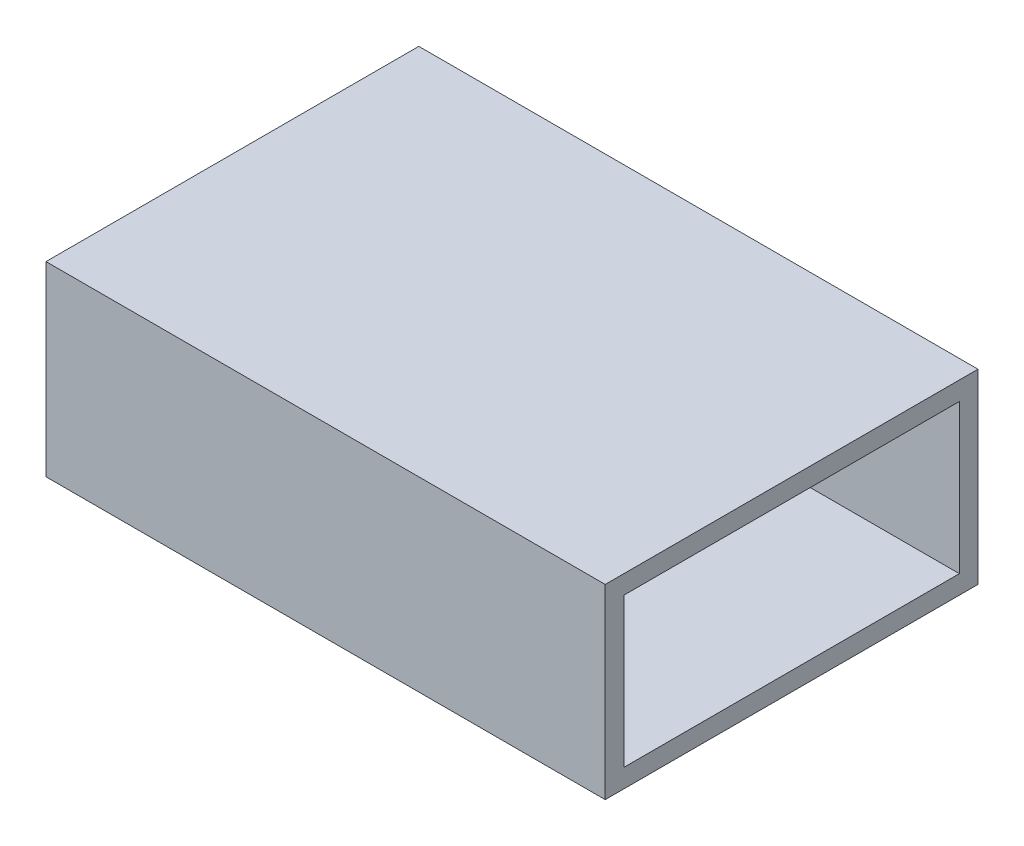
SolidWorks part; units mm, degrees
ref_plane "Front Plane" through (0, 0, 0) normal (0, 0, 1) x (1, 0, 0)
ref_plane "Top Plane" through (0, 0, 0) normal (0, 1, 0) x (1, 0, 0)
ref_plane "Right Plane" through (0, 0, 0) normal (1, 0, 0) x (0, 0, -1)
sketch3d "3DSketch1"
  line L0 (-38.1, 0, 0) -> (38.1, 0, 0)
  point P4 (0, 0, 0)
  dimension "D1" = 76.2
other "Versaframe VERSAFRAME 2 X 1 X 0.1 (1)"
ref_plane "Plane1" through (-38.1, 0, 0) normal (1, 0, 0) x (0, 1, 0)
sketch "Sketch1" plane through (-38.1, 0, 0) normal (1, 0, 0) x (0, 1, 0)
  line L0 (-10.16, 22.86) -> (-10.16, -22.86)
  line L1 (-12.7, 25.4) -> (12.7, 25.4)
  line L2 (-12.7, 25.4) -> (-12.7, -25.4)
  line L3 (-12.7, -25.4) -> (12.7, -25.4)
  line L4 (12.7, 25.4) -> (12.7, -25.4)
  line L5 (-12.7, 25.4) -> (12.7, -25.4) construction
  line L6 (-12.7, -25.4) -> (12.7, 25.4) construction
  line L7 (-10.16, -22.86) -> (10.16, -22.86)
  line L8 (10.16, 22.86) -> (10.16, -22.86)
  line L9 (-10.16, 22.86) -> (10.16, 22.86)
  line L10 (0, 25.4) -> (0, -25.4) construction
  line L12 (12.7, 0) -> (-12.7, 0) construction
  point P0 (0, 0)
  point P12 (0, 22.86)
  point P15 (-10.16, 0)
  point P16 (10.16, 0)
  point P17 (0, -22.86)
  point P18 (0, 0)
  dimension "D1" = 25.4
  dimension "D2" = 50.8
  dimension "D3" = 2.54
